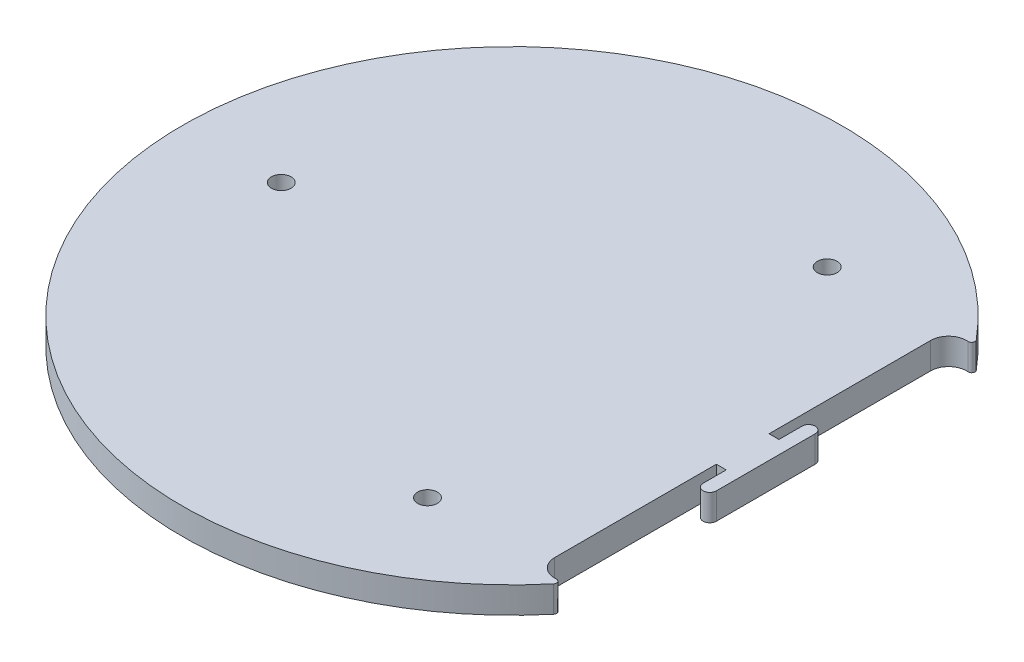
SolidWorks part; units mm, degrees
ref_plane "Alzado" through (0, 0, 0) normal (0, 0, 1) x (1, 0, 0)
ref_plane "Planta" through (0, 0, 0) normal (0, 1, 0) x (1, 0, 0)
ref_plane "Vista lateral" through (0, 0, 0) normal (1, 0, 0) x (0, 0, -1)
sketch "Croquis1" plane through (0, 0, 0) normal (0, 1, 0) x (1, 0, 0)
  line L0 (-50, 0) -> (35, 0) construction
  line L1 (36.5, -28.5161) -> (36.5, -4) construction
  line L2 (37.5, -28.5161) -> (37.5, 28.5161) construction
  line L3 (35, -28.5161) -> (35, -4)
  line L4 (37.5, 0) -> (36.5, 0) construction
  line L5 (37.5, 7.5) -> (36.5, 7.5) construction
  line L6 (37.5, -6.5) -> (36.5, -6.5) construction
  line L7 (37.5, -7.5) -> (37.5, 7.5) construction
  line L8 (36.5, -7.5) -> (36.5, -4)
  line L9 (38.5, -7.5) -> (38.5, 7.5)
  line L10 (-50, -4) -> (35, -4) construction
  line L11 (-50, 4) -> (35, 4) construction
  line L12 (35, 4) -> (36.5, 4)
  line L13 (35, -4) -> (36.5, -4)
  line L14 (35, 4) -> (35, 28.5161)
  line L15 (35, -28.5161) -> (35, 28.5161) construction
  line L16 (36.5, 4) -> (36.5, 28.5161) construction
  line L17 (36.5, -28.5161) -> (36.5, 28.5161) construction
  line L18 (36.5, 7.5) -> (36.5, 4)
  arc A0 (38.3792, 32.0474) -> (38.3792, -32.0474) centre (0, 0) ccw
  arc A1 (36.5, -7.5) -> (38.5, -7.5) centre (37.5, -7.5) ccw
  arc A2 (37.9494, 31.2228) -> (35, 28.5161) centre (37.7167, 28.5161) ccw
  arc A3 (37.9494, 31.2228) -> (38.3792, 32.0474) centre (37.9926, 31.7246) ccw
  arc A4 (37.9494, -31.2228) -> (38.3792, -32.0474) centre (37.9926, -31.7246) cw
  arc A5 (37.9494, -31.2228) -> (35, -28.5161) centre (37.7167, -28.5161) cw
  arc A6 (38.5, 7.5) -> (36.5, 7.5) centre (37.5, 7.5) ccw
  point P25 (37.5, 0)
  dimension "D1" = 100
  dimension "D2" = 1.5
  dimension "D3" = 85
  dimension "D5" = 14
  dimension "D4" = 1
  dimension "D6" = 4
  dimension "D7" = 4
extrude "Saliente-Extruir1" add sketch "Croquis1" along normal mid plane 4
sketch "Croquis2" plane through (0, -2, 0) normal (0, -1, 0) x (1, 0, 0)
  line L0 (0, 0) -> (37.7172, 65.3282) construction
  line L1 (0, 0) -> (37.7172, -65.3282) construction
  line L3 (0, 0) -> (-75.4345, 0) construction
  arc A0 (38.3792, 32.0474) -> (38.3792, -32.0474) centre (0, 0) ccw construction
  arc A1 (38.3792, 32.0474) -> (38.3792, -32.0474) centre (0, 0) ccw
  arc A2 (26.8654, 22.4332) -> (26.8654, -22.4332) centre (0, 0) ccw construction
  circle A3 centre (17.5, 30.3109) radius 1.5
  circle A4 centre (-35, 0) radius 1.5
  circle A5 centre (17.5, -30.3109) radius 1.5
  point P4 (17.5, 30.3109)
  point P5 (17.5, -30.3109)
  point P19 (0, 0)
  dimension "D2" = 3
  dimension "D1" = 15
  dimension "D3" = 3
extrude "Cortar-Extruir1" cut sketch "Croquis2" against normal blind 7 contours A4 | A5 | A3
sketch "Croquis3" plane through (0, -2, 0) normal (0, -1, 0) x (1, 0, 0)
  circle A3 centre (17.5, 30.3109) radius 3
  circle A4 centre (17.5, -30.3109) radius 3
  circle A5 centre (-35, 0) radius 3
  circle A6 centre (-35, 0) radius 4
  circle A7 centre (17.5, 30.3109) radius 4
  circle A8 centre (17.5, -30.3109) radius 4
  circle A9 centre (17.5, 30.3109) radius 1.5 construction
  circle A10 centre (17.5, -30.3109) radius 1.5 construction
  dimension "D1" = 8
  dimension "D2" = 6
extrude "Saliente-Extruir2" add sketch "Croquis3" along normal blind 5
sketch "Croquis4" plane through (0, 2, 0) normal (0, 1, 0) x (1, 0, 0)
  line L0 (38.5, 0) -> (31.0315, 0) construction
  line L1 (38.5, -7.5) -> (38.5, 7.5) construction
